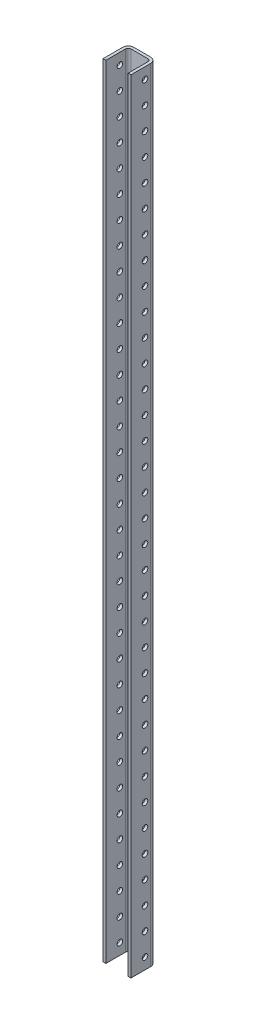
SolidWorks part; units mm, degrees
material "Plain Carbon Steel"
ref_plane "Front Plane" through (0, 0, 0) normal (0, 0, 1) x (1, 0, 0)
ref_plane "Top Plane" through (0, 0, 0) normal (0, 1, 0) x (1, 0, 0)
ref_plane "Rithe Plane" through (0, 0, 0) normal (1, 0, 0) x (0, 0, -1)
sketch "Sketch1" plane through (0, 0, 0) normal (0, 1, 0) x (1, 0, 0)
  line L0 (0, 103.632) -> (0, -110.3752) construction
  line L1 (-12.7, 0) -> (-12.7, 22.225)
  line L2 (-9.525, 25.4) -> (9.525, 25.4)
  line L3 (12.7, 22.225) -> (12.7, 0)
  line L4 (12.7, 0) -> (15.875, 0)
  line L5 (15.875, 0) -> (15.875, 22.225)
  line L6 (9.525, 28.575) -> (-9.525, 28.575)
  line L7 (-15.875, 22.225) -> (-15.875, 0)
  line L8 (-15.875, 0) -> (-12.7, 0)
  arc A0 (-12.7, 22.225) -> (-9.525, 25.4) centre (-9.525, 22.225) cw
  arc A1 (12.7, 22.225) -> (9.525, 25.4) centre (9.525, 22.225) ccw
  arc A2 (9.525, 28.575) -> (15.875, 22.225) centre (9.525, 22.225) cw
  arc A3 (-15.875, 22.225) -> (-9.525, 28.575) centre (-9.525, 22.225) cw
  dimension "D5" = 3.175
  dimension "D6" = 6.35
  dimension "D1" = 31.75
  dimension "D2" = 25.4
  dimension "D3" = 28.575
  dimension "D4" = 25.4
extrude "Extrude1" add sketch "Sketch1" along normal mid plane 889
sketch "Sketch2" plane through (0, 0, -28.575) normal (0, 0, -1) x (-1, 0, 0)
  line L0 (0, 461.5657) -> (0, -466.4615) construction
  line L1 (-9.525, 444.5) -> (9.525, 444.5) construction
  line L2 (-9.525, -444.5) -> (9.525, -444.5) construction
  circle A0 centre (0, 444.5) radius 1.59 construction
  circle A1 centre (-1.905, 361.95) radius 4.826
  circle A2 centre (-1.905, 336.55) radius 4.826
  circle A3 centre (-1.905, 107.95) radius 4.826
  circle A4 centre (-1.905, 82.55) radius 4.826
  circle A5 centre (1.905, 0) radius 4.826
  circle A6 centre (-1.905, -361.95) radius 4.826
  circle A7 centre (-1.905, -336.55) radius 4.826
  circle A8 centre (-1.905, -82.55) radius 4.826
  circle A9 centre (-1.905, -107.95) radius 4.826
  circle A10 centre (0, -241.3) radius 1.5875
  dimension "D1" = 3.18
  dimension "D2" = 3.175
  dimension "D6" = 9.652
  dimension "D11" = 9.652
  dimension "D14" = 95.25
  dimension "D3" = 1.905
  dimension "D4" = 82.55
  dimension "D5" = 25.4
  dimension "D7" = 25.4
  dimension "D8" = 254
  dimension "D9" = 1.905
  dimension "D10" = 444.5
  dimension "D12" = 82.55
  dimension "D13" = 25.4
  dimension "D15" = 25.4
  dimension "D16" = 228.6
extrude "Extrude2" cut sketch "Sketch2" against normal blind 25
sketch "Sketch3" plane through (15.875, 0, 0) normal (1, 0, 0) x (0, 0, -1)
  line L1 (28.575, 444.5) -> (28.575, -444.5) construction
  circle A0 centre (15.875, 431.8) radius 3.175
  circle A1 centre (15.875, 406.4) radius 3.175
  circle A2 centre (15.875, 381) radius 3.175
  circle A3 centre (15.875, 355.6) radius 3.175
  circle A4 centre (15.875, 330.2) radius 3.175
  circle A5 centre (15.875, 304.8) radius 3.175
  circle A6 centre (15.875, 279.4) radius 3.175
  circle A7 centre (15.875, 254) radius 3.175
  circle A8 centre (15.875, 228.6) radius 3.175
  circle A9 centre (15.875, 203.2) radius 3.175
  circle A10 centre (15.875, 177.8) radius 3.175
  circle A11 centre (15.875, 152.4) radius 3.175
  circle A12 centre (15.875, 127) radius 3.175
  circle A13 centre (15.875, 101.6) radius 3.175
  circle A14 centre (15.875, 76.2) radius 3.175
  circle A15 centre (15.875, 50.8) radius 3.175
  circle A16 centre (15.875, 25.4) radius 3.175
  circle A17 centre (15.875, 0) radius 3.175
  circle A18 centre (15.875, -25.4) radius 3.175
  circle A19 centre (15.875, -50.8) radius 3.175
  circle A20 centre (15.875, -76.2) radius 3.175
  circle A21 centre (15.875, -101.6) radius 3.175
  circle A22 centre (15.875, -127) radius 3.175
  circle A23 centre (15.875, -152.4) radius 3.175
  circle A24 centre (15.875, -177.8) radius 3.175
  circle A25 centre (15.875, -203.2) radius 3.175
  circle A26 centre (15.875, -228.6) radius 3.175
  circle A27 centre (15.875, -254) radius 3.175
  circle A28 centre (15.875, -279.4) radius 3.175
  circle A29 centre (15.875, -304.8) radius 3.175
  circle A30 centre (15.875, -330.2) radius 3.175
  circle A31 centre (15.875, -355.6) radius 3.175
  circle A32 centre (15.875, -381) radius 3.175
  circle A33 centre (15.875, -406.4) radius 3.175
  circle A34 centre (15.875, -431.8) radius 3.175
  dimension "D1" = 6.35
  dimension "D2" = 12.7
  dimension "D3" = 12.7
  dimension "D4" = 25.4
extrude "Extrude3" cut sketch "Sketch3" against normal blind 35
